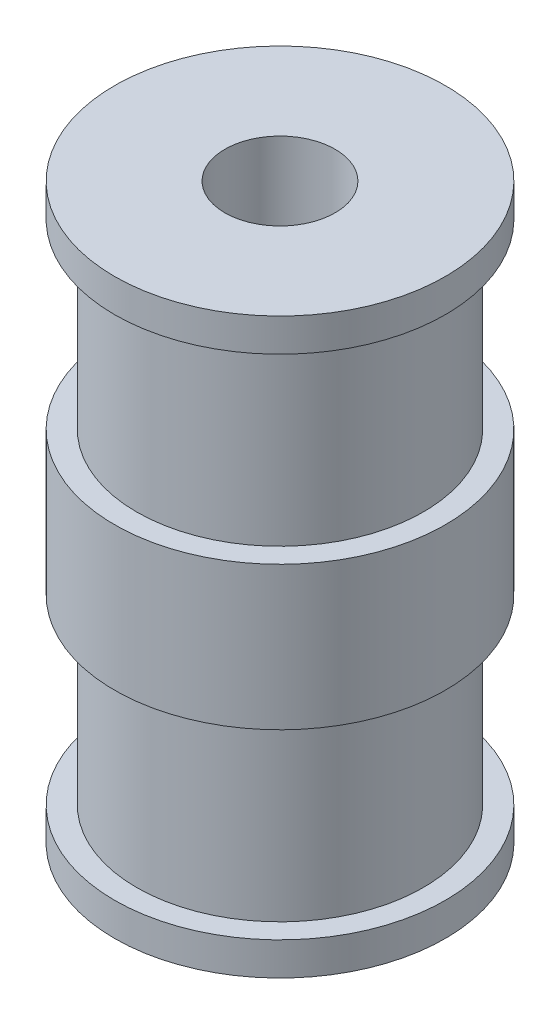
SolidWorks part; units mm, degrees
ref_plane "Front Plane" through (0, 0, 0) normal (0, 0, 1) x (1, 0, 0)
ref_plane "Top Plane" through (0, 0, 0) normal (0, 1, 0) x (1, 0, 0)
ref_plane "Right Plane" through (0, 0, 0) normal (1, 0, 0) x (0, 0, -1)
sketch "Sketch1" plane through (0, 0, 0) normal (0, 1, 0) x (1, 0, 0)
  circle A0 centre (0, 0) radius 2.5
  circle A1 centre (0, 0) radius 7.5
  dimension "D1" = 5
  dimension "D2" = 15
extrude "Boss-Extrude1" add sketch "Sketch1" along normal blind 1.5
sketch "Sketch2" plane through (0, 1.5, 0) normal (0, 1, 0) x (1, 0, 0)
  circle A0 centre (0, 0) radius 2.5
  circle A1 centre (0, 0) radius 6.5
  dimension "D1" = 13
extrude "Boss-Extrude2" add sketch "Sketch2" along normal blind 8.25
sketch "Sketch3" plane through (0, 9.75, 0) normal (0, 1, 0) x (1, 0, 0)
  circle A0 centre (0, 0) radius 2.5
  circle A1 centre (0, 0) radius 7.5
extrude "Boss-Extrude3" add sketch "Sketch3" along normal blind 6.5
sketch "Sketch4" plane through (0, 16.25, 0) normal (0, 1, 0) x (1, 0, 0)
  circle A0 centre (0, 0) radius 2.5
  circle A1 centre (0, 0) radius 6.5
  dimension "D1" = 13
extrude "Boss-Extrude4" add sketch "Sketch4" along normal blind 8.25
sketch "Sketch5" plane through (0, 24.5, 0) normal (0, 1, 0) x (1, 0, 0)
  circle A0 centre (0, 0) radius 2.5
  circle A1 centre (0, 0) radius 7.5
extrude "Boss-Extrude5" add sketch "Sketch5" along normal blind 1.5
